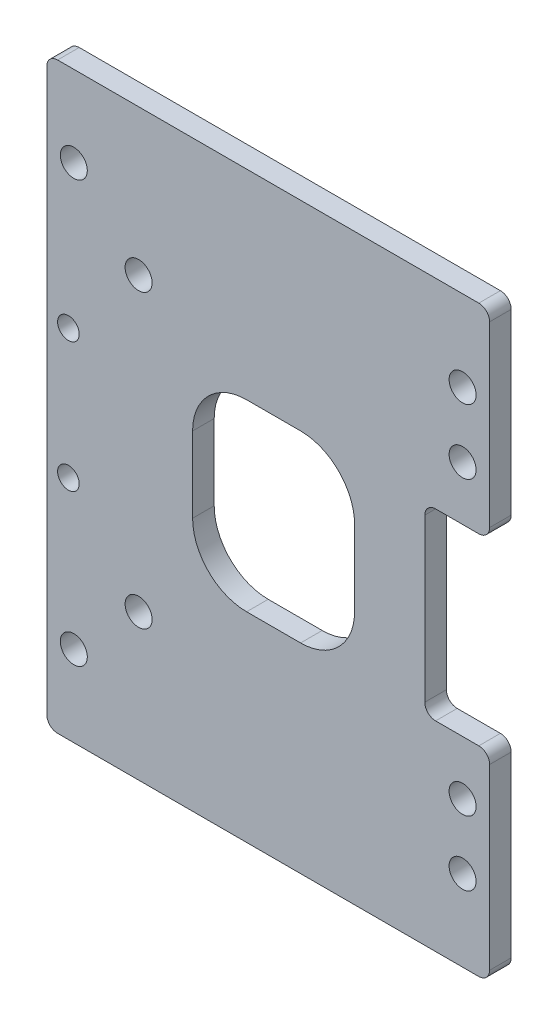
SolidWorks part; units mm, degrees
material "自訂玻璃纖維"
ref_plane "前基準面" through (0, 0, 0) normal (0, 0, 1) x (1, 0, 0)
ref_plane "上基準面" through (0, 0, 0) normal (0, 1, 0) x (1, 0, 0)
ref_plane "右基準面" through (0, 0, 0) normal (1, 0, 0) x (0, 0, -1)
sketch "草圖1" plane through (0, 0, 0) normal (0, 0, 1) x (1, 0, 0)
  line L0 (25.7147, 4.0447) -> (25.7147, -0.9553)
  line L1 (3.2147, 22.0447) -> (8.2147, 22.0447)
  line L2 (-1.7853, 17.0447) -> (-1.7853, 10.0447)
  line L3 (3.2147, 5.0447) -> (8.2147, 5.0447)
  line L4 (13.2147, 17.0447) -> (13.2147, 10.0447)
  line L5 (-14.2853, 40.5447) -> (24.7147, 40.5447)
  line L6 (-15.2853, 39.5447) -> (-15.2853, 23.5447)
  line L7 (25.7147, 39.5447) -> (25.7147, 28.5447)
  line L8 (25.7147, 28.5447) -> (25.7147, 23.0447)
  line L9 (24.7147, 22.0447) -> (20.7147, 22.0447)
  line L10 (25.7147, -0.9553) -> (25.7147, -12.4553)
  line L11 (24.7147, 5.0447) -> (20.7147, 5.0447)
  line L12 (19.7147, 21.0447) -> (19.7147, 6.0447)
  line L13 (24.7147, -13.4553) -> (-14.2853, -13.4553)
  line L14 (-15.2853, 23.5447) -> (-15.2853, 3.5447)
  line L21 (-15.2853, 3.5447) -> (-15.2853, -12.4553)
  circle A0 centre (-6.7853, 27.0447) radius 1.25
  circle A1 centre (23.2147, 27.0447) radius 1.25
  circle A2 centre (-6.7853, 0.0447) radius 1.25
  circle A3 centre (23.2147, 0.0447) radius 1.25
  arc A5 (-1.7853, 10.0447) -> (3.2147, 5.0447) centre (3.2147, 10.0447) ccw
  arc A6 (8.2147, 5.0447) -> (13.2147, 10.0447) centre (8.2147, 10.0447) ccw
  arc A7 (8.2147, 22.0447) -> (13.2147, 17.0447) centre (8.2147, 17.0447) cw
  arc A8 (3.2147, 22.0447) -> (-1.7853, 17.0447) centre (3.2147, 17.0447) ccw
  arc A9 (25.7147, 4.0447) -> (24.7147, 5.0447) centre (24.7147, 4.0447) ccw
  arc A10 (20.7147, 5.0447) -> (19.7147, 6.0447) centre (20.7147, 6.0447) cw
  arc A11 (20.7147, 22.0447) -> (19.7147, 21.0447) centre (20.7147, 21.0447) ccw
  arc A12 (24.7147, 22.0447) -> (25.7147, 23.0447) centre (24.7147, 23.0447) ccw
  arc A13 (24.7147, 40.5447) -> (25.7147, 39.5447) centre (24.7147, 39.5447) cw
  arc A14 (-15.2853, 39.5447) -> (-14.2853, 40.5447) centre (-14.2853, 39.5447) cw
  arc A15 (25.7147, -12.4553) -> (24.7147, -13.4553) centre (24.7147, -12.4553) cw
  arc A16 (-15.2853, -12.4553) -> (-14.2853, -13.4553) centre (-14.2853, -12.4553) ccw
  circle A17 centre (-12.7853, 33.0447) radius 1.25
  circle A18 centre (23.2147, 33.0447) radius 1.25
  circle A19 centre (23.2147, -5.9553) radius 1.25
  circle A20 centre (-12.7853, -5.9553) radius 1.25
  circle A21 centre (-13.2853, 19.5447) radius 1
  circle A22 centre (-13.2853, 7.5447) radius 1
  point P32 (25.7147, 5.0447)
  point P35 (19.7147, 5.0447)
  point P48 (-15.2853, 40.5447)
  point P53 (-15.2853, -13.4553)
  dimension "D1" = 2.5
  dimension "D2" = 30
  dimension "D3" = 30
  dimension "D4" = 27
  dimension "D5" = 27
  dimension "D13" = 0
  dimension "D14" = 5
  dimension "D20" = 1
  dimension "D21" = 1
  dimension "D22" = 2.5
  dimension "D23" = 7.5
  dimension "D24" = 2.5
  dimension "D25" = 2.5
  dimension "D26" = 7.5
  dimension "D27" = 2.5
  dimension "D28" = 7.5
  dimension "D29" = 7.5
  dimension "D30" = 12
  dimension "D9" = 5
  dimension "D10" = 10
  dimension "D11" = 5
  dimension "D12" = 5
  dimension "D15" = 54
  dimension "D18" = 2.5
  dimension "D19" = 6
extrude "填料-伸長1" add sketch "草圖1" along normal blind 2
